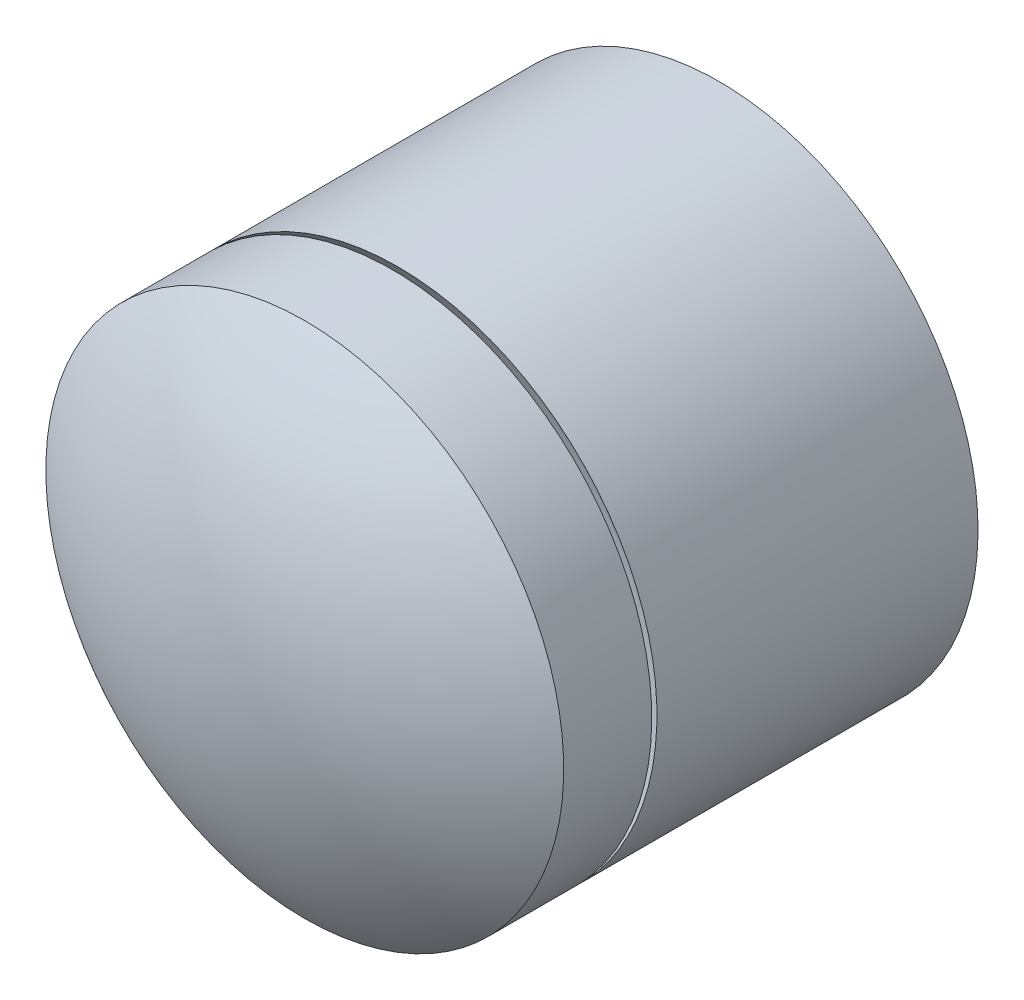
SolidWorks part; units mm, degrees
material "Glass"
ref_plane "前视基准面" through (0, 0, 0) normal (0, 0, 1) x (1, 0, 0)
ref_plane "上视基准面" through (0, 0, 0) normal (0, 1, 0) x (1, 0, 0)
ref_plane "右视基准面" through (0, 0, 0) normal (1, 0, 0) x (0, 0, -1)
sketch "草图1" plane through (0, 0, 0) normal (1, 0, 0) x (0, 0, -1)
  line L0 (-1, 0) -> (3.7731, 0) construction
  line L1 (0, 0) -> (-1, 1) construction
  line L2 (-0.5, 1) -> (-0.5, -0.5) construction
  line L3 (0.93, 1) -> (-0.31, 1)
  line L5 (-0.49, -0.49) -> (-0.5, -0.5) construction
  line L6 (1, 1) -> (0, 0) construction
  line L7 (-1, 0) -> (-4.8172, 0) construction
  line L8 (-0.49, 1) -> (-0.49, -0.49) construction
  line L9 (-0.33, 1) -> (-0.67, 1)
  line L11 (-1, 0) -> (0, 0)
  line L12 (0.998, 0) -> (0.02, 0)
  arc A0 (-0.67, 1) -> (-1, 0) centre (0.68, 0) ccw
  arc A2 (-0.33, 1) -> (0, 0) centre (-1.68, 0) cw
  arc A3 (-0.31, 1) -> (0.02, 0) centre (-1.66, 0) cw
  arc A4 (0.998, 0) -> (0.93, 1) centre (-6.392, 0) ccw
  point P0 (0, 0)
  dimension "D3" = 3.36
  dimension "D4" = 1.6
  dimension "D1" = 2
  dimension "D7" = 0.01
revolve "旋转1" add sketch "草图1" angle 360 about L11
